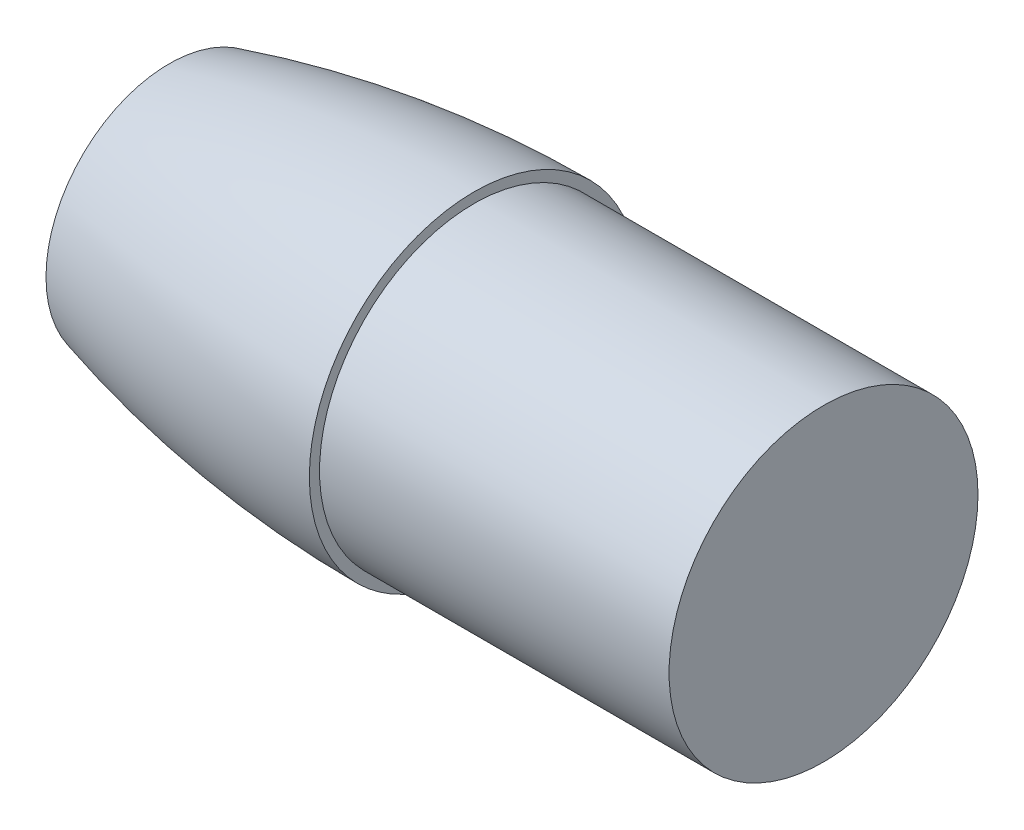
SolidWorks part; units mm, degrees
ref_plane "Front Plane" through (0, 0, 0) normal (0, 0, 1) x (1, 0, 0)
ref_plane "Top Plane" through (0, 0, 0) normal (0, 1, 0) x (1, 0, 0)
ref_plane "Right Plane" through (0, 0, 0) normal (1, 0, 0) x (0, 0, -1)
sketch "Sketch1" plane through (0, 0, 0) normal (0, 0, 1) x (1, 0, 0)
  line L0 (0, 0) -> (0, 240.1279) construction
  line L1 (-150, 240.1279) -> (-140.3343, 240.1279)
  line L2 (0, 278.1279) -> (0, 280.6279)
  line L3 (81, 240.1279) -> (86, 240.1279)
  line L4 (86, 240.1279) -> (86, 278.1279)
  line L5 (86, 278.1279) -> (0, 278.1279)
  line L6 (0, 278.1279) -> (0, 280.6279) construction
  line L9 (81, 245.1279) -> (81, 273.1279)
  line L10 (81, 273.1279) -> (-5, 273.1279)
  line L11 (-5, 273.1279) -> (-5, 278.083)
  line L12 (81, 245.1279) -> (81, 240.1279)
  line L13 (-131.4056, 245.1279) -> (0, 245.1279) construction
  line L14 (0, 245.1279) -> (81, 245.1279) construction
  line L15 (-150, 240.1279) -> (0, 240.1279) construction
  line L16 (0, 240.1279) -> (86, 240.1279) construction
  line L17 (-150, 240.1279) -> (-175.3476, 240.1279) construction
  line L18 (-140.3343, 240.1279) -> (-75, 240.1279) construction
  line L19 (-75, 267.8248) -> (-75, 270.4201)
  line L20 (0, 278.1279) -> (0, 283.1279) construction
  arc A1 (-5, 278.083) -> (-75, 267.8248) centre (0, 0) ccw
  arc A3 (-5, 278.083) -> (-75, 267.8248) centre (0, 0) ccw
  arc A5 (-5, 278.083) -> (-75, 267.8248) centre (0, 0) ccw
  arc A6 (-5.0449, 280.5826) -> (-75, 270.4201) centre (0, 0) ccw
  arc A7 (-5.0449, 280.5826) -> (-75, 270.4201) centre (0, 0) ccw
  arc A8 (-5.0449, 280.5826) -> (-75, 270.4201) centre (0, 0) ccw
  arc A9 (0, 280.6279) -> (-75, 270.4201) centre (0, 0) ccw
  arc A10 (0, 283.1279) -> (-150, 240.1279) centre (0, 0) ccw construction
  arc A11 (-5.0449, 280.5826) -> (-132.5868, 247.3313) centre (0, 0) ccw construction
  arc A12 (-5.0449, 280.5826) -> (-141.5957, 242.2863) centre (0, 0) ccw construction
  arc A13 (-5, 278.083) -> (-131.4056, 245.1279) centre (0, 0) ccw construction
  arc A14 (-5, 278.083) -> (-140.3343, 240.1279) centre (0, 0) ccw construction
  dimension "D1" = 150
  dimension "D2" = 75
  dimension "D4" = 5
  dimension "D5" = 86
  dimension "D6" = 2.5
revolve "Revolve1" add sketch "Sketch1" angle 360 about L17
